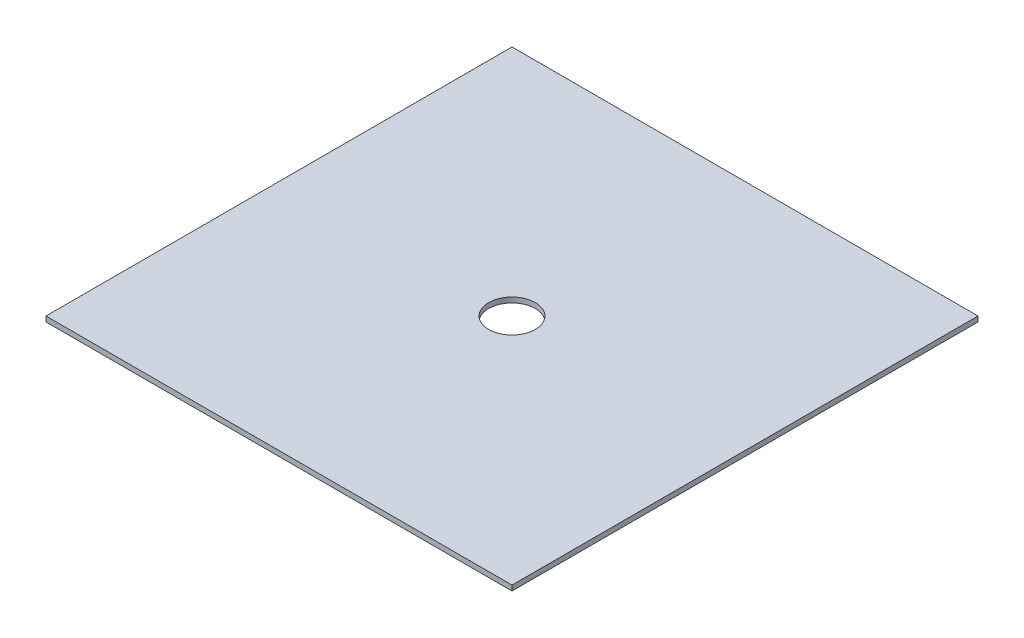
SolidWorks part; units mm, degrees
ref_plane "Front Plane" through (0, 0, 0) normal (0, 0, 1) x (1, 0, 0)
ref_plane "Top Plane" through (0, 0, 0) normal (0, 1, 0) x (1, 0, 0)
ref_plane "Right Plane" through (0, 0, 0) normal (1, 0, 0) x (0, 0, -1)
sketch "Sketch1" plane through (0, 0, 0) normal (0, 1, 0) x (1, 0, 0)
  line L0 (0, 285.75) -> (0, -285.75) construction
  line L1 (-285.75, 285.75) -> (285.75, 285.75)
  line L2 (-285.75, 285.75) -> (-285.75, -285.75)
  line L3 (-285.75, -285.75) -> (285.75, -285.75)
  line L4 (285.75, 285.75) -> (285.75, -285.75)
  line L5 (-285.75, 0) -> (285.75, 0) construction
  circle A0 centre (0, 0) radius 28.575
  point P6 (0, 0)
  dimension "D3" = 57.15
  dimension "D1" = 571.5
  dimension "D2" = 571.5
extrude "Boss-Extrude1" add sketch "Sketch1" along normal blind 6.35
